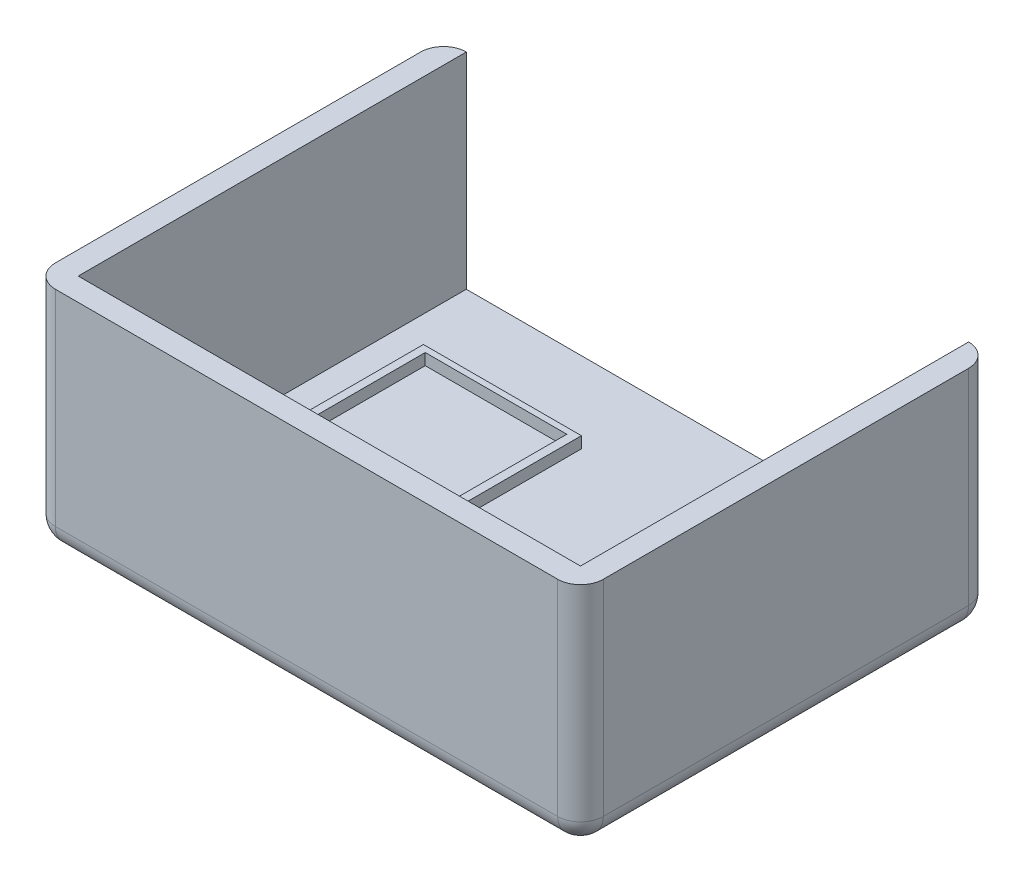
SolidWorks part; units mm, degrees
ref_plane "Front Plane" through (0, 0, 0) normal (0, 0, 1) x (1, 0, 0)
ref_plane "Top Plane" through (0, 0, 0) normal (0, 1, 0) x (1, 0, 0)
ref_plane "Right Plane" through (0, 0, 0) normal (1, 0, 0) x (0, 0, -1)
sketch "Sketch2" plane through (0, 0, 0) normal (0, 1, 0) x (1, 0, 0)
  line L1 (-28.9548, 18.9266) -> (211.0452, 18.9266)
  line L2 (-28.9548, 18.9266) -> (-28.9548, -161.0734)
  line L3 (-28.9548, -161.0734) -> (211.0452, -161.0734)
  line L4 (211.0452, 18.9266) -> (211.0452, -161.0734)
  line L5 (-28.9548, 18.9266) -> (211.0452, -161.0734) construction
  line L6 (-28.9548, -161.0734) -> (211.0452, 18.9266) construction
  point P0 (91.0452, -71.0734)
  dimension "D1" = 240
  dimension "D2" = 180
extrude "Boss-Extrude1" add sketch "Sketch2" along normal blind 100 contours L1 L4 L3 L2
shell "Shell1" thickness 10
fillet "Fillet3" radius 10 4 edges at (-28.9548, 50, -18.9266) (-28.9548, 50, 161.0734) (211.0452, 50, -18.9266) (211.0452, 50, 161.0734)
fillet "Fillet4" radius 10 8 edges at (208.1163, 0, -15.9976) (91.0452, 0, -18.9266) (-26.0259, 0, -15.9976) (-28.9548, 0, 71.0734) (-26.0259, 0, 158.1445) (91.0452, 0, 161.0734) (208.1163, 0, 158.1445) (211.0452, 0, 71.0734)
sketch "Sketch3" plane through (0, 0, -18.9266) normal (0, 0, -1) x (-1, 0, 0)
  line L1 (-201.0452, 100) -> (18.9548, 100)
  line L2 (-201.0452, 100) -> (-201.0452, 10)
  line L3 (-201.0452, 10) -> (18.9548, 10)
  line L4 (18.9548, 100) -> (18.9548, 10)
extrude "Cut-Extrude1" cut sketch "Sketch3" against normal blind 10
sketch "Sketch6" plane through (0, 10, 0) normal (0, 1, 0) x (1, 0, 0)
  line L0 (-18.9548, 18.9266) -> (-18.9548, -151.0734) construction
  line L1 (1.0452, -19.0734) -> (63.0452, -19.0734)
  line L2 (1.0452, -19.0734) -> (1.0452, -111.0734)
  line L3 (1.0452, -111.0734) -> (63.0452, -111.0734)
  line L4 (63.0452, -19.0734) -> (63.0452, -111.0734)
  line L5 (-18.9548, -151.0734) -> (201.0452, -151.0734) construction
  line L7 (-2.4029, -16.4325) -> (66.8037, -16.4325)
  line L8 (-2.4029, -16.4325) -> (-2.4029, -114.36)
  line L9 (-2.4029, -114.36) -> (66.8037, -114.36)
  line L10 (66.8037, -16.4325) -> (66.8037, -114.36)
  line L11 (114.5564, -77.6805) -> (190.5564, -77.6805)
  line L12 (114.5564, -77.6805) -> (114.5564, -118.6805)
  line L13 (114.5564, -118.6805) -> (190.5564, -118.6805)
  line L14 (190.5564, -77.6805) -> (190.5564, -118.6805)
  line L15 (110.404, -73.182) -> (194.8361, -73.182)
  line L16 (110.404, -73.182) -> (110.404, -123.7029)
  line L17 (110.404, -123.7029) -> (194.8361, -123.7029)
  line L18 (194.8361, -73.182) -> (194.8361, -123.7029)
  dimension "D1" = 92
  dimension "62mm" = 62
  dimension "D2" = 40
  dimension "D3" = 76
  dimension "20mm" = 20
  dimension "D4" = 41
extrude "Boss-Extrude2" add sketch "Sketch6" along normal blind 5
